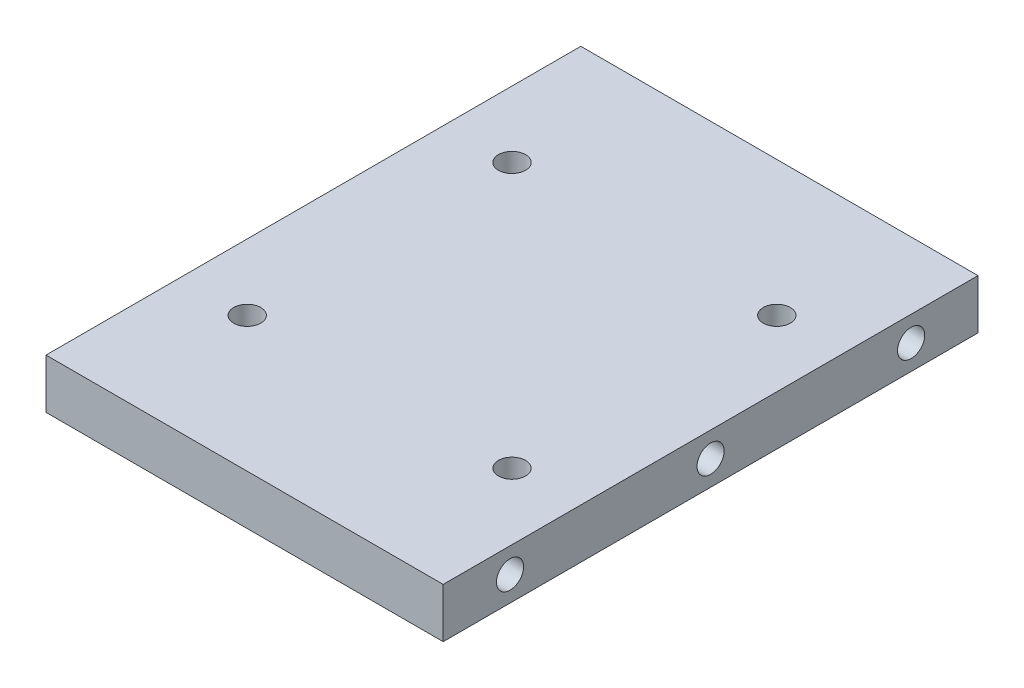
SolidWorks part; units mm, degrees
ref_plane "Front Plane" through (0, 0, 0) normal (0, 0, 1) x (1, 0, 0)
ref_plane "Top Plane" through (0, 0, 0) normal (0, 1, 0) x (1, 0, 0)
ref_plane "Right Plane" through (0, 0, 0) normal (1, 0, 0) x (0, 0, -1)
sketch "Sketch1" plane through (0, 69.975, 0) normal (0, 1, 0) x (1, 0, 0)
  line L0 (-38.1, -51.3017) -> (-47.625, -51.3017)
  line L1 (-38.1, -51.3017) -> (-47.625, -51.3017) construction
  line L4 (38.1, 51.3017) -> (-38.1, 51.3017)
  line L5 (-38.1, -51.3017) -> (38.1, -51.3017)
  line L6 (47.625, -51.3017) -> (38.1, -51.3017)
  line L7 (47.625, -51.3017) -> (38.1, -51.3017) construction
  line L8 (-47.625, 51.3017) -> (-38.1, 51.3017)
  line L9 (-47.625, 51.3017) -> (-38.1, 51.3017) construction
  line L10 (38.1, 51.3017) -> (47.625, 51.3017)
  line L11 (38.1, 51.3017) -> (47.625, 51.3017) construction
  line L12 (38.1, 51.3017) -> (38.1, -51.3017)
  line L13 (-38.1, -51.3017) -> (-38.1, 51.3017)
  line L15 (-25.4, 25.4) -> (25.4, 25.4) construction
  line L16 (-25.4, 25.4) -> (-25.4, -25.4) construction
  line L17 (-25.4, -25.4) -> (25.4, -25.4) construction
  line L18 (25.4, 25.4) -> (25.4, -25.4) construction
  line L19 (-25.4, 25.4) -> (25.4, -25.4) construction
  line L20 (-25.4, -25.4) -> (25.4, 25.4) construction
  circle A0 centre (25.4, -25.4) radius 2.6035
  circle A1 centre (-25.4, -25.4) radius 2.6035
  circle A2 centre (-25.4, 25.4) radius 2.6035
  circle A3 centre (25.4, 25.4) radius 2.6035
  point P8 (0, 0)
  point P24 (0, 0)
  dimension "D1" = 5.207
  dimension "D2" = 50.8
  dimension "D3" = 4
extrude "Boss-Extrude1" add sketch "Sketch1" along normal blind 9.525
sketch "Sketch2" plane through (-38.1, 0, 0) normal (-1, 0, 0) x (0, 0, 1)
  line L0 (0, 69.975) -> (0, 79.5) construction
  line L1 (0, 69.975) -> (-51.3017, 79.5) construction
  line L2 (-25.6508, 74.7375) -> (-51.3017, 74.7375) construction
  line L4 (-51.3017, 69.975) -> (51.3017, 69.975)
  line L5 (51.3017, 69.975) -> (51.3017, 79.5)
  line L6 (51.3017, 79.5) -> (-51.3017, 79.5)
  line L7 (-51.3017, 79.5) -> (-51.3017, 69.975)
  line L8 (-51.3017, 69.975) -> (51.3017, 69.975) construction
  line L9 (51.3017, 69.975) -> (51.3017, 79.5) construction
  line L10 (51.3017, 79.5) -> (-51.3017, 79.5) construction
  line L11 (-51.3017, 79.5) -> (-51.3017, 69.975) construction
  circle A0 centre (0, 74.7375) radius 2.6035
  circle A1 centre (-38.4762, 74.7375) radius 2.6035
  circle A2 centre (38.4762, 74.7375) radius 2.6035
  dimension "D2" = 5.207
  dimension "D1" = 0
extrude "Cut-Extrude1" cut sketch "Sketch2" against normal through all
